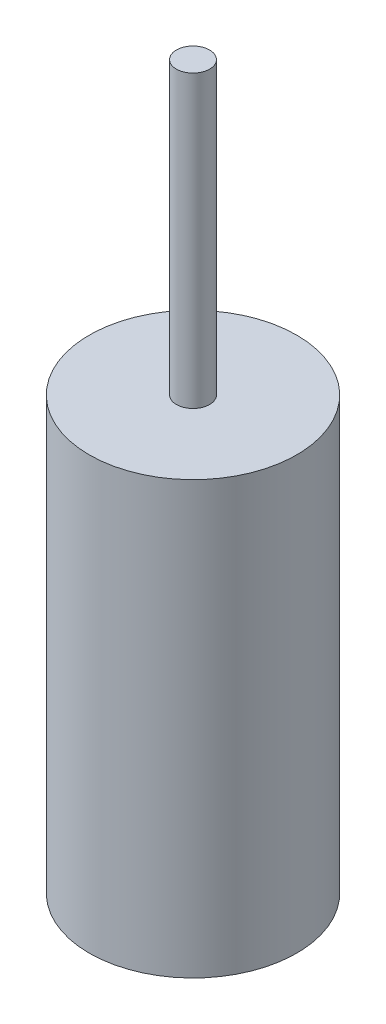
SolidWorks part; units mm, degrees
ref_plane "Front Plane" through (0, 0, 0) normal (0, 0, 1) x (1, 0, 0)
ref_plane "Top Plane" through (0, 0, 0) normal (0, 1, 0) x (1, 0, 0)
ref_plane "Right Plane" through (0, 0, 0) normal (1, 0, 0) x (0, 0, -1)
sketch "Sketch1" plane through (0, 0, 0) normal (0, 1, 0) x (1, 0, 0)
  circle A0 centre (0, 0) radius 12.5
  dimension "D1" = 25
extrude "Boss-Extrude1" add sketch "Sketch1" along normal blind 52
sketch "Sketch2" plane through (0, 52, 0) normal (0, 1, 0) x (1, 0, 0)
  circle A0 centre (0, 0) radius 2
extrude "Boss-Extrude2" add sketch "Sketch2" along normal blind 35
